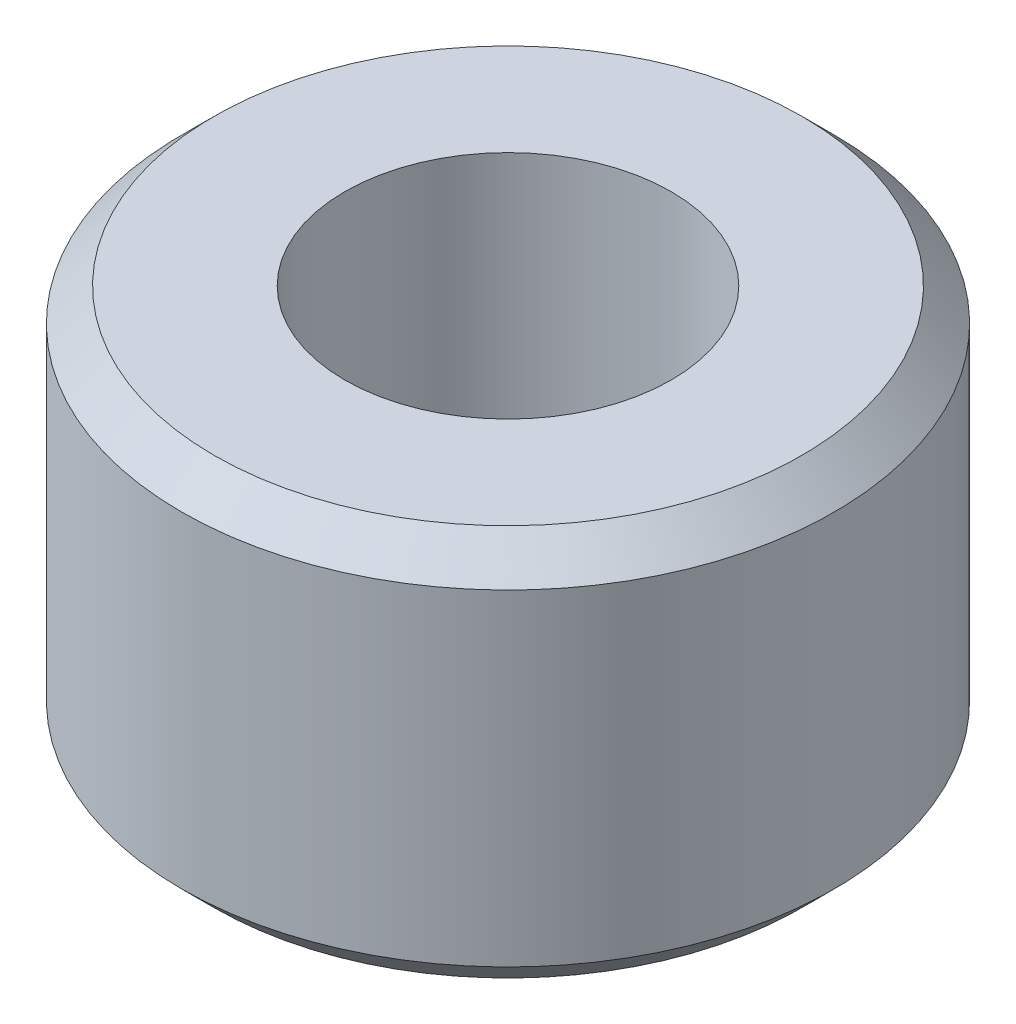
SolidWorks part; units mm, degrees
ref_plane "Front Plane" through (0, 0, 0) normal (0, 0, 1) x (1, 0, 0)
ref_plane "Top Plane" through (0, 0, 0) normal (0, 1, 0) x (1, 0, 0)
ref_plane "Right Plane" through (0, 0, 0) normal (1, 0, 0) x (0, 0, -1)
sketch "Sketch1" plane through (0, 0, 0) normal (0, 1, 0) x (1, 0, 0)
  circle A0 centre (0, 0) radius 6.35
  circle A1 centre (0, 0) radius 3.175
  dimension "D1" = 6.35
  dimension "D2" = 3.175
extrude "Boss-Extrude1" add sketch "Sketch1" along normal blind 7.62
chamfer "Chamfer1" distance 0.635 angle 45 2 edges at (0, 0, 6.35) (0, 7.62, 6.35)
